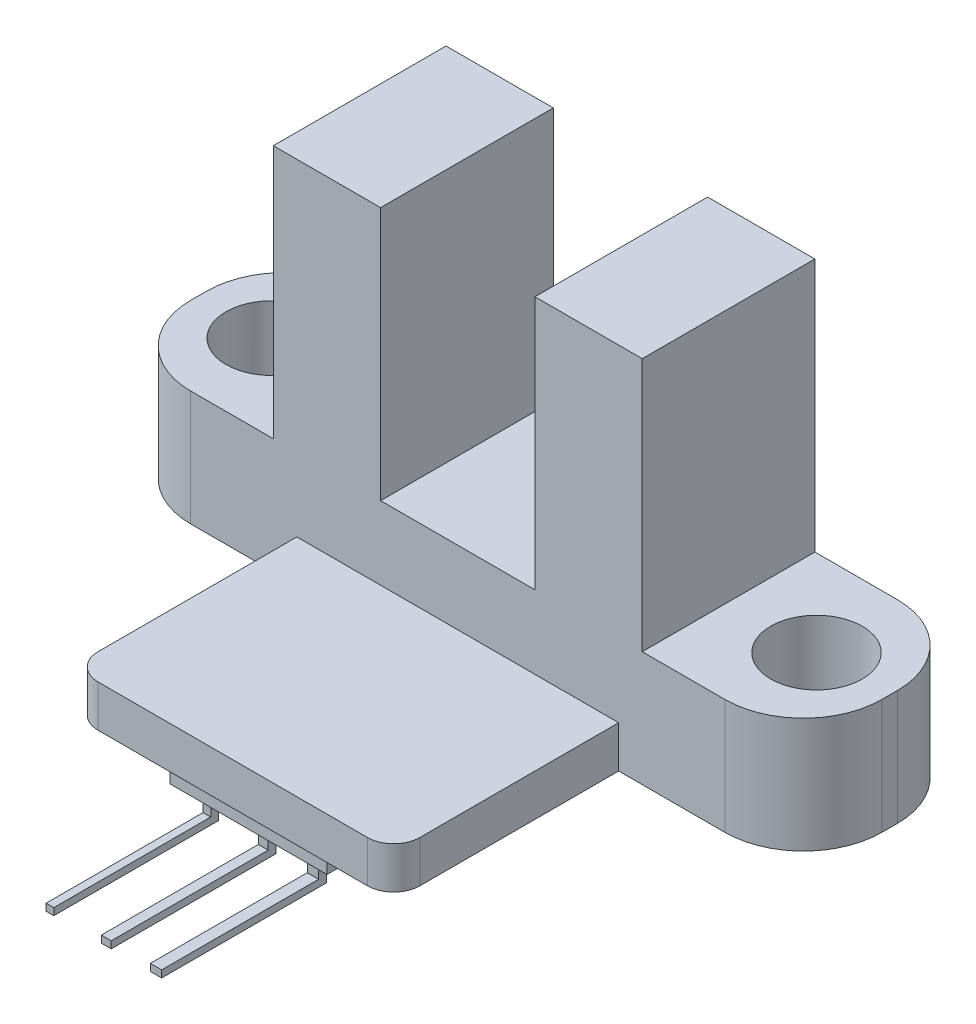
SolidWorks part; units mm, degrees
ref_plane "前视基准面" through (0, 0, 0) normal (0, 0, 1) x (1, 0, 0)
ref_plane "上视基准面" through (0, 0, 0) normal (0, 1, 0) x (1, 0, 0)
ref_plane "右视基准面" through (0, 0, 0) normal (1, 0, 0) x (0, 0, -1)
other "Configuration Table"
sketch "草图1" plane through (0, 0, 0) normal (0, 1, 0) x (1, 0, 0)
  line L1 (0, 0) -> (26.42, 0)
  line L2 (0, 0) -> (0, 6.6)
  line L3 (0, 6.6) -> (26.42, 6.6)
  line L4 (26.42, 0) -> (26.42, 6.6)
  dimension "D1" = 6.6
  dimension "D2" = 26.42
extrude "凸台-拉伸1" add sketch "草图1" along normal blind 4.4
sketch "草图2" plane through (0, 0, 0) normal (0, -1, 0) x (-1, 0, 0)
  line L0 (0, 0) -> (-26.42, 0) construction
  line L1 (-7.06, 0) -> (-19.36, 0)
  line L2 (-7.06, 0) -> (-7.06, -8.6)
  line L3 (-7.06, -8.6) -> (-19.36, -8.6)
  line L4 (-19.36, 0) -> (-19.36, -8.6)
  line L5 (-26.42, 6.6) -> (0, 6.6) construction
  point P6 (-13.21, 0)
  point P9 (-13.21, 6.6)
  dimension "D1" = 8.6
  dimension "D2" = 12.3
  dimension "D3" = 0
extrude "凸台-拉伸2" add sketch "草图2" against normal blind 1.6
sketch "草图3" plane through (0, 4.4, 0) normal (0, 1, 0) x (1, 0, 0)
  line L0 (26.42, 6.6) -> (0, 6.6) construction
  line L1 (6.16, 6.6) -> (10.26, 6.6)
  line L2 (6.16, 6.6) -> (6.16, 0)
  line L3 (6.16, 0) -> (10.26, 0)
  line L4 (10.26, 6.6) -> (10.26, 0)
  line L5 (0, 0) -> (26.42, 0) construction
  line L6 (0, 6.6) -> (0, 0) construction
  line L7 (16.16, 6.6) -> (20.26, 6.6)
  line L8 (16.16, 6.6) -> (16.16, 0)
  line L9 (16.16, 0) -> (20.26, 0)
  line L10 (20.26, 6.6) -> (20.26, 0)
  dimension "D1" = 4.1
  dimension "D2" = 4.1
  dimension "D3" = 5.9
  dimension "D4" = 6.16
extrude "凸台-拉伸3" add sketch "草图3" along normal blind 9.7
fillet "圆角1" radius 3 4 edges at (26.42, 2.2, -6.6) (26.42, 2.2, 0) (0, 2.2, -6.6) (0, 2.2, 0)
fillet "圆角2" radius 1 2 edges at (19.36, 0.8, 8.6) (7.06, 0.8, 8.6)
sketch "草图4" plane through (0, 0, 0) normal (0, -1, 0) x (-1, 0, 0)
  line L1 (-10.21, -8) -> (-16.21, -8)
  line L2 (-10.21, -8) -> (-10.21, -7)
  line L3 (-10.21, -7) -> (-16.21, -7)
  line L4 (-16.21, -8) -> (-16.21, -7)
  line L6 (-18.36, -8.6) -> (-8.06, -8.6) construction
  point P6 (-13.21, -8.6)
  point P7 (-13.21, -7)
  dimension "D1" = 1
  dimension "D2" = 6
  dimension "D3" = 0
  dimension "D4" = 0.6
extrude "凸台-拉伸4" add sketch "草图4" along normal blind 1
sketch "草图5" plane through (0, -1, 0) normal (0, -1, 0) x (-1, 0, 0)
  line L1 (-11.0599, -7.5848) -> (-11.3531, -7.5848)
  line L2 (-11.0599, -7.5848) -> (-11.0599, -7.2916)
  line L3 (-11.0599, -7.2916) -> (-11.3531, -7.2916)
  line L4 (-11.3531, -7.5848) -> (-11.3531, -7.2916)
  line L5 (-13.1707, -7.5848) -> (-13.5479, -7.5848)
  line L6 (-13.1707, -7.5848) -> (-13.1707, -7.2916)
  line L7 (-13.1707, -7.2916) -> (-13.5479, -7.2916)
  line L8 (-13.5479, -7.5848) -> (-13.5479, -7.2916)
  line L9 (-15.0428, -7.5848) -> (-15.4759, -7.5848)
  line L10 (-15.0428, -7.5848) -> (-15.0428, -7.2916)
  line L11 (-15.0428, -7.2916) -> (-15.4759, -7.2916)
  line L12 (-15.4759, -7.5848) -> (-15.4759, -7.2916)
extrude "凸台-拉伸5" add sketch "草图5" along normal blind 1
sketch "草图6" plane through (0, 0, 7.5848) normal (0, 0, 1) x (1, 0, 0)
  line L0 (11.3531, -2) -> (11.3531, -1) construction
  line L1 (11.0599, -2) -> (11.3531, -2)
  line L2 (11.0599, -2) -> (11.0599, -1.732)
  line L3 (11.0599, -1.732) -> (11.3531, -1.732)
  line L4 (11.3531, -2) -> (11.3531, -1.732)
  line L5 (13.5479, -2) -> (13.5479, -1) construction
  line L6 (13.1707, -2) -> (13.5479, -2)
  line L7 (13.1707, -2) -> (13.1707, -1.732)
  line L8 (13.1707, -1.732) -> (13.5479, -1.732)
  line L9 (13.5479, -2) -> (13.5479, -1.732)
  line L10 (15.4759, -2) -> (15.4759, -1) construction
  line L11 (15.0428, -2) -> (15.4759, -2)
  line L12 (15.0428, -2) -> (15.0428, -1.732)
  line L13 (15.0428, -1.732) -> (15.4759, -1.732)
  line L14 (15.4759, -2) -> (15.4759, -1.732)
extrude "凸台-拉伸6" add sketch "草图6" along normal blind 6
sketch "草图7" plane through (0, 4.4, 0) normal (0, 1, 0) x (1, 0, 0)
  line L0 (26.42, 3) -> (26.42, 3.6) construction
  line L1 (0, 3.6) -> (0, 3) construction
  circle A0 centre (2.8, 3.3) radius 1.75
  circle A1 centre (23.62, 3.3) radius 1.75
  dimension "D1" = 3.5
  dimension "D2" = 3.5
  dimension "D3" = 2.8
  dimension "D4" = 2.8
extrude "切除-拉伸1" cut sketch "草图7" against normal blind 6
equation "\"D4@草图3\"=\"D2@草图1\"/2-\"D1@草图3\"-\"D3@草图3\"/2"
